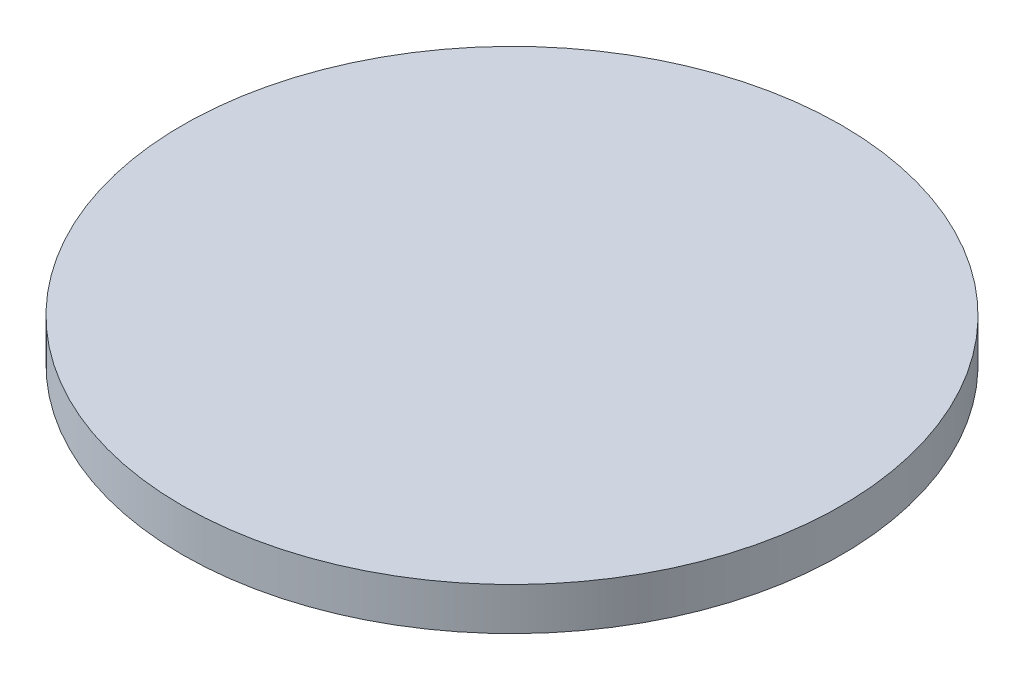
SolidWorks part; units mm, degrees
ref_plane "Front Plane" through (0, 0, 0) normal (0, 0, 1) x (1, 0, 0)
ref_plane "Top Plane" through (0, 0, 0) normal (0, 1, 0) x (1, 0, 0)
ref_plane "Right Plane" through (0, 0, 0) normal (1, 0, 0) x (0, 0, -1)
sketch "Sketch1" plane through (0, 0, 0) normal (0, 1, 0) x (1, 0, 0)
  circle A0 centre (-90.6762, 17.2924) radius 49.2125
  dimension "D1" = 98.425
extrude "Boss-Extrude1" add sketch "Sketch1" along normal blind 6.35
